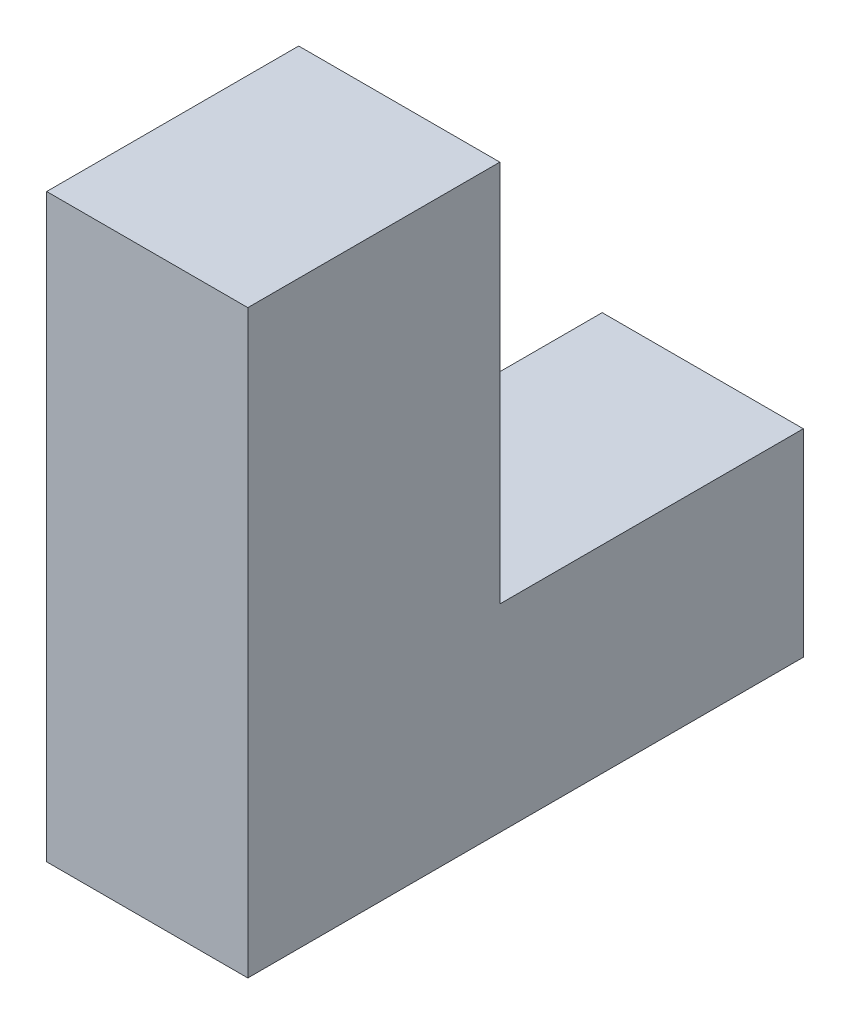
SolidWorks part; units mm, degrees
ref_plane "Спереди" through (0, 0, 0) normal (0, 0, 1) x (1, 0, 0)
ref_plane "Сверху" through (0, 0, 0) normal (0, 1, 0) x (1, 0, 0)
ref_plane "Справа" through (0, 0, 0) normal (1, 0, 0) x (0, 0, -1)
sketch "Эскиз1" plane through (0, 0, 0) normal (1, 0, 0) x (0, 0, -1)
  line L0 (0, -14.695) -> (0, 43.0353)
  line L1 (0, 43.0353) -> (25.0602, 43.0353)
  line L2 (25.0602, 43.0353) -> (25.0602, 4.9858)
  line L3 (25.0602, 4.9858) -> (55.2374, 4.9858)
  line L4 (55.2374, 4.9858) -> (55.2374, -14.695)
  line L5 (55.2374, -14.695) -> (0, -14.695)
extrude "Бобышка-Вытянуть1" add sketch "Эскиз1" along normal mid plane 20
ref_plane "face_for_mating" through (0, 0, 0) normal (0, 0, 1) x (1, 0, 0)
ref_plane "face_for_horizont" through (0, -14.695, 0) normal (0, -1, 0) x (-1, 0, 0)
